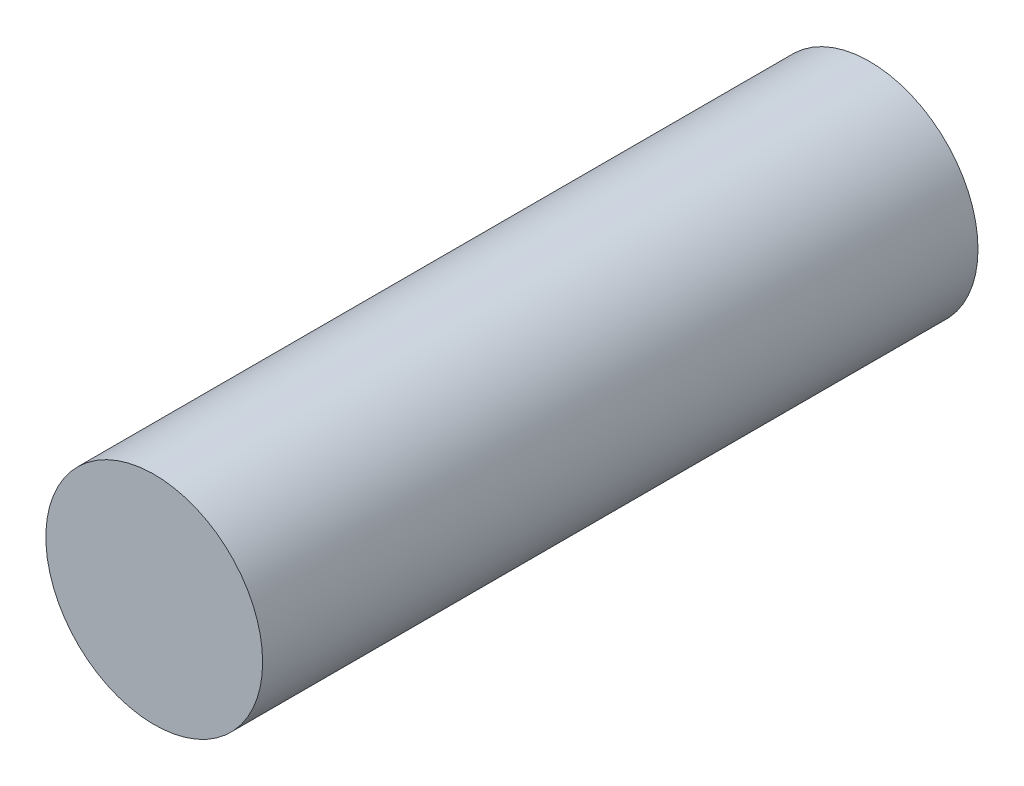
SolidWorks part; units mm, degrees
ref_plane "Front Plane" through (0, 0, 0) normal (0, 0, 1) x (1, 0, 0)
ref_plane "Top Plane" through (0, 0, 0) normal (0, 1, 0) x (1, 0, 0)
ref_plane "Right Plane" through (0, 0, 0) normal (1, 0, 0) x (0, 0, -1)
sketch "Sketch2" plane through (0, 0, 0) normal (0, 0, 1) x (1, 0, 0)
  circle A0 centre (0, 0) radius 6.35
  dimension "D1" = 12.7
extrude "Boss-Extrude1" add sketch "Sketch2" along normal blind 41.91
